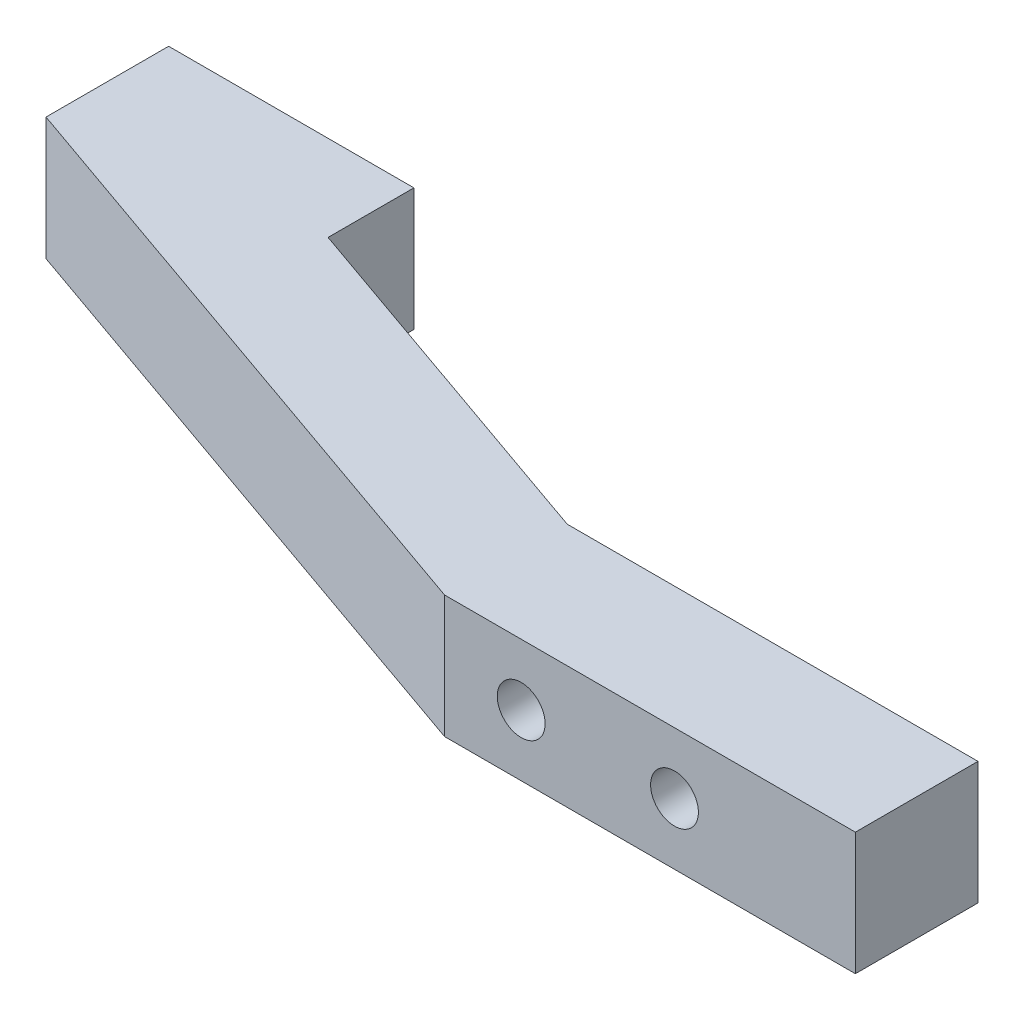
SolidWorks part; units mm, degrees
ref_plane "Front Plane" through (0, 0, 0) normal (0, 0, 1) x (1, 0, 0)
ref_plane "Top Plane" through (0, 0, 0) normal (0, 1, 0) x (1, 0, 0)
ref_plane "Right Plane" through (0, 0, 0) normal (1, 0, 0) x (0, 0, -1)
sketch "Sketch3" plane through (0, 0, 0) normal (0, 0, 1) x (1, 0, 0)
  line L1 (0, 0) -> (13.4, 0)
  line L2 (0, 0) -> (0, 4)
  line L3 (0, 4) -> (13.4, 4)
  line L4 (13.4, 0) -> (13.4, 4)
  circle A0 centre (2.5, 2) radius 0.78
  circle A1 centre (7.5, 2) radius 0.78
  dimension "D5" = 1.56
  dimension "D6" = 1.56
  dimension "D1" = 4
  dimension "D2" = 13.4
  dimension "D3" = 2.5
  dimension "D4" = 7.5
extrude "Boss-Extrude1" add sketch "Sketch3" along normal blind 4
sketch "Sketch4" plane through (0, 4, 0) normal (0, 1, 0) x (1, 0, 0)
  line L0 (13.4, -4) -> (0, -4) construction
  line L1 (0, -4) -> (0, 0) construction
  line L2 (0, 0) -> (13.4, 0) construction
  line L3 (0, 0) -> (0, 4) construction
  line L4 (0, 4) -> (13.4, 4) construction
  line L5 (13.4, 0) -> (13.4, 4) construction
  line L6 (0, 4) -> (0, 8) construction
  line L11 (0, -4) -> (-20, 3)
  line L12 (0, 10) -> (13.4, 10) construction
  line L13 (0, 10) -> (0, 6) construction
  line L14 (0, 6) -> (13.4, 6) construction
  line L15 (13.4, 10) -> (13.4, 6) construction
  line L16 (0, 10) -> (13.4, 6) construction
  line L17 (0, 6) -> (13.4, 10) construction
  line L18 (-20, 3) -> (-20, 6)
  line L19 (-20, 6) -> (-12, 6)
  line L20 (-12, 6) -> (-12, 4.2)
  line L21 (-12, 4.2) -> (0, 0)
  line L26 (13.4, 0) -> (0, 0)
  line L27 (0, 0) -> (0, -4)
  line L28 (0, -4) -> (13.4, -4)
  line L29 (13.4, -4) -> (13.4, 0)
  line L31 (0, 0) -> (0, -4)
  point P6 (6.7, 8)
  point P14 (0, 8)
  dimension "D1" = 4
  dimension "D2" = 4
  dimension "D3" = 4
  dimension "D4" = 20
  dimension "D5" = 8
  dimension "D6" = 3
  dimension "D7" = 0
extrude "Boss-Extrude2" add sketch "Sketch4" against normal blind 4
sketch "Sketch5" plane through (0, 0, -6) normal (0, 0, -1) x (-1, 0, 0)
  line L1 (12, 4) -> (20, 4)
  line L2 (12, 4) -> (12, 0)
  line L3 (12, 0) -> (20, 0)
  line L4 (20, 4) -> (20, 0)
extrude "Boss-Extrude3" add sketch "Sketch5" along normal blind 1
